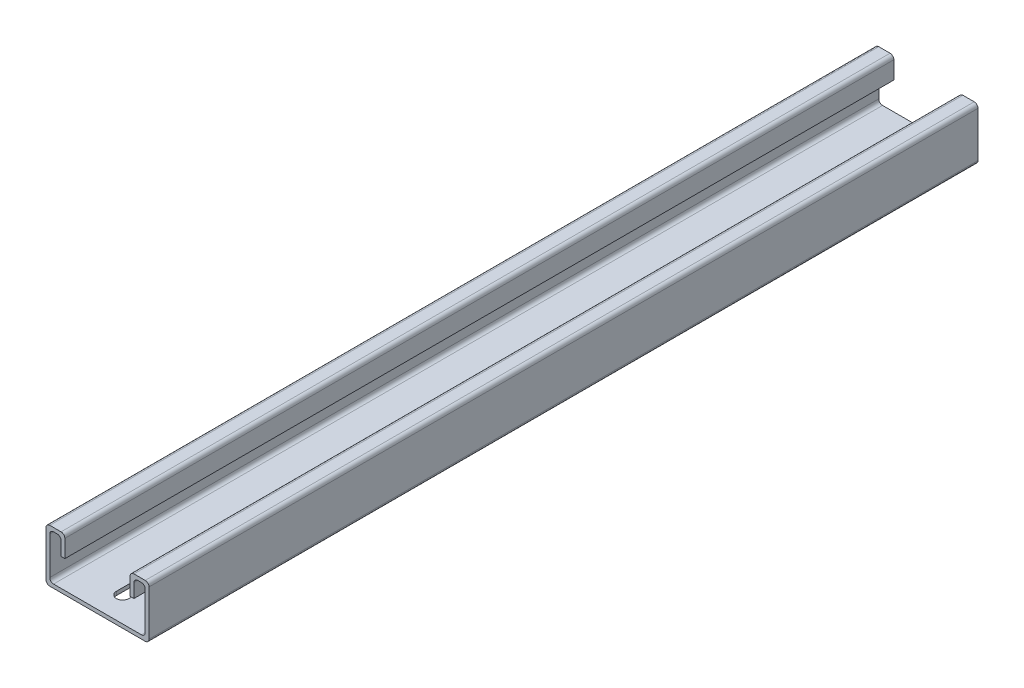
SolidWorks part; units mm, degrees
material "1345 合金"
ref_plane "前视基准面" through (0, 0, 0) normal (0, 0, 1) x (1, 0, 0)
ref_plane "上视基准面" through (0, 0, 0) normal (0, 1, 0) x (1, 0, 0)
ref_plane "右视基准面" through (0, 0, 0) normal (1, 0, 0) x (0, 0, -1)
sketch "草图1" plane through (0, 0, 0) normal (0, 0, 1) x (1, 0, 0)
  line L0 (-19, 10.5) -> (-14.5, 10.5)
  line L5 (-19, -10.5) -> (19, -10.5)
  line L6 (-20.5, -9) -> (-20.5, 9)
  line L7 (-19, 10.5) -> (19, 10.5) construction
  line L8 (20.5, -9) -> (20.5, 9)
  line L9 (-20.5, -10.5) -> (20.5, 10.5) construction
  line L10 (-20.5, 10.5) -> (20.5, -10.5) construction
  line L11 (19, 10.5) -> (14.5, 10.5)
  line L12 (13, 9) -> (13, 2)
  line L13 (-13, 9) -> (-13, 2)
  line L14 (-13, 2) -> (-14.5, 2)
  line L15 (13, 2) -> (14.5, 2)
  line L16 (-14.5, 2) -> (-14.5, 7.5)
  line L17 (-16, 9) -> (-17.5, 9)
  line L18 (-19, 7.5) -> (-19, -7.5)
  line L19 (-17.5, -9) -> (17.5, -9)
  line L20 (19, -7.5) -> (19, 7.5)
  line L21 (17.5, 9) -> (16, 9)
  line L22 (14.5, 7.5) -> (14.5, 2)
  arc A4 (19, -10.5) -> (20.5, -9) centre (19, -9) ccw
  arc A5 (19, 10.5) -> (20.5, 9) centre (19, 9) cw
  arc A6 (-20.5, 9) -> (-19, 10.5) centre (-19, 9) cw
  arc A7 (-19, -10.5) -> (-20.5, -9) centre (-19, -9) cw
  arc A8 (-14.5, 10.5) -> (-13, 9) centre (-14.5, 9) cw
  arc A9 (14.5, 10.5) -> (13, 9) centre (14.5, 9) ccw
  arc A10 (19, 7.5) -> (17.5, 9) centre (17.5, 7.5) ccw
  arc A11 (17.5, -9) -> (19, -7.5) centre (17.5, -7.5) ccw
  arc A12 (-19, -7.5) -> (-17.5, -9) centre (-17.5, -7.5) ccw
  arc A13 (-17.5, 9) -> (-19, 7.5) centre (-17.5, 7.5) ccw
  arc A14 (-14.5, 7.5) -> (-16, 9) centre (-16, 7.5) ccw
  arc A15 (16, 9) -> (14.5, 7.5) centre (16, 7.5) ccw
  point P0 (0, 0)
  point P26 (-13, 10.5)
  point P29 (13, 10.5)
  dimension "D3" = 1.5
  dimension "D5" = 1.5
  dimension "D7" = 1.5
  dimension "D12" = 1.5
  dimension "D13" = 1.5
  dimension "D14" = 1.5
  dimension "D1" = 41
  dimension "D2" = 21
  dimension "D4" = 6
  dimension "D6" = 6
  dimension "D8" = 7
  dimension "D9" = 7
  dimension "D10" = 1.5
  dimension "D11" = 1.5
sketch "草图3" plane through (0, 0, 0) normal (0, 1, 0) x (1, 0, 0)
  line L0 (0, -17.9231) -> (0, -5.9632) construction
  line L1 (0, -10) -> (0, -30) construction
  line L2 (2.5, -10) -> (2.5, -30)
  line L3 (-2.5, -10) -> (-2.5, -30)
  line L4 (0, -10) -> (0, 0) construction
  line L5 (0, -30) -> (0, -45) construction
  line L6 (0, -45) -> (0, -65) construction
  line L7 (2.5, -45) -> (2.5, -65)
  line L8 (-2.5, -45) -> (-2.5, -65)
  line L9 (0, -65) -> (0, -80) construction
  line L10 (0, -155) -> (0, -175) construction
  line L13 (2.5, -155) -> (2.5, -175)
  line L14 (-2.5, -155) -> (-2.5, -175)
  line L15 (0, -320) -> (0, -300) construction
  line L16 (-2.5, -320) -> (-2.5, -300)
  line L17 (2.5, -320) -> (2.5, -300)
  line L18 (0, -300) -> (0, -285) construction
  line L19 (0, -285) -> (0, -265) construction
  line L20 (-2.5, -285) -> (-2.5, -265)
  line L21 (2.5, -285) -> (2.5, -265)
  arc A0 (2.5, -10) -> (-2.5, -10) centre (0, -10) ccw
  arc A1 (-2.5, -30) -> (2.5, -30) centre (0, -30) ccw
  arc A2 (2.5, -45) -> (-2.5, -45) centre (0, -45) ccw
  arc A3 (-2.5, -65) -> (2.5, -65) centre (0, -65) ccw
  arc A6 (2.5, -155) -> (-2.5, -155) centre (0, -155) ccw
  arc A7 (-2.5, -175) -> (2.5, -175) centre (0, -175) ccw
  arc A8 (-2.5, -320) -> (2.5, -320) centre (0, -320) ccw
  arc A9 (2.5, -300) -> (-2.5, -300) centre (0, -300) ccw
  arc A10 (-2.5, -285) -> (2.5, -285) centre (0, -285) ccw
  arc A11 (2.5, -265) -> (-2.5, -265) centre (0, -265) ccw
  point P5 (0, -20)
  point P14 (0, -55)
  point P24 (0, -155)
  point P25 (0, -165)
  point P30 (0, -320)
  point P33 (0, -310)
  point P41 (0, -275)
  point P46 (-131.4487, -99.9972)
  point P47 (-142.3755, -163.9969)
  dimension "D1" = 2.5
  dimension "D5" = 2.5
  dimension "D7" = 2.5
  dimension "D10" = 2.5
  dimension "D13" = 2.5
  dimension "D2" = 20
  dimension "D3" = 10
  dimension "D4" = 15
  dimension "D6" = 20
  dimension "D8" = 20
  dimension "D9" = 20
  dimension "D11" = 15
  dimension "D12" = 20
  dimension "D14" = 110
  dimension "D15" = 110
extrude "凸台-拉伸1" add sketch "草图1" along normal blind 330
extrude "切除-拉伸1" cut sketch "草图3" against normal through all
